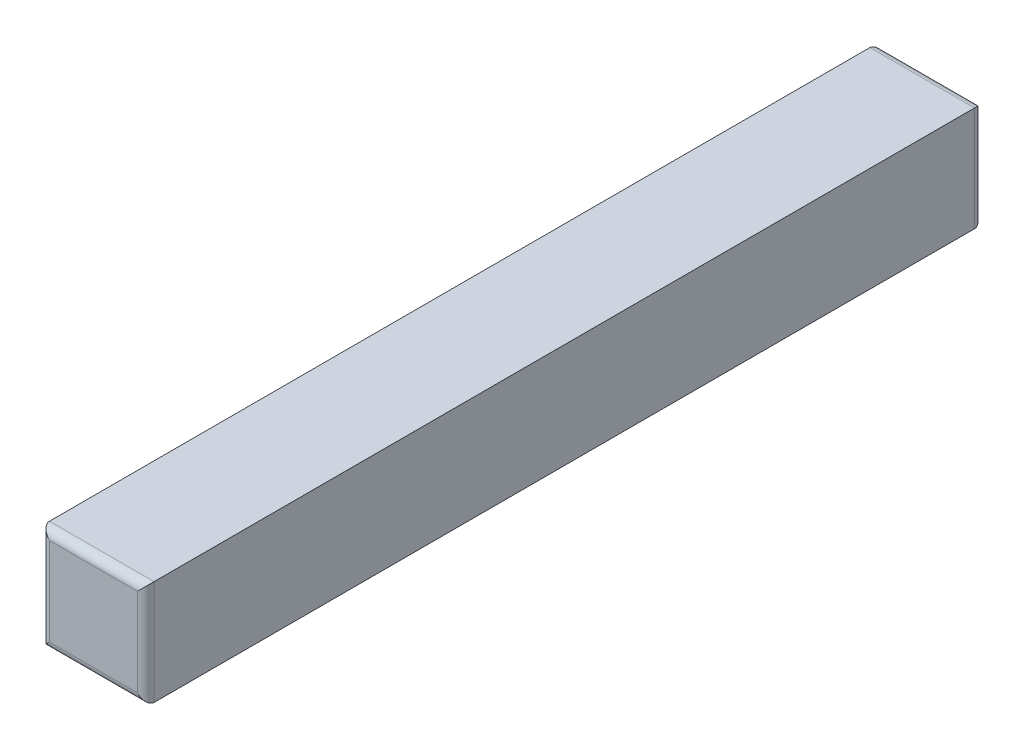
SolidWorks part; units mm, degrees
ref_plane "Front Plane" through (0, 0, 0) normal (0, 0, 1) x (1, 0, 0)
ref_plane "Top Plane" through (0, 0, 0) normal (0, 1, 0) x (1, 0, 0)
ref_plane "Right Plane" through (0, 0, 0) normal (1, 0, 0) x (0, 0, -1)
sketch "Sketch1" plane through (0, 0, 0) normal (0, 0, 1) x (1, 0, 0)
  line L1 (0, 0) -> (3.175, 0)
  line L2 (0, 0) -> (0, 3.175)
  line L3 (0, 3.175) -> (3.175, 3.175)
  line L4 (3.175, 0) -> (3.175, 3.175)
  dimension "D1" = 3.175
  dimension "D2" = 3.175
extrude "Boss-Extrude1" add sketch "Sketch1" against normal blind 25.4
fillet "Fillet1" radius 0.254 4 edges at (1.5875, 3.175, 0) (3.175, 1.5875, 0) (1.5875, 0, 0) (0, 1.5875, 0)
fillet "Fillet2" radius 0.254 4 edges at (1.5875, 0, -25.4) (3.175, 1.5875, -25.4) (1.5875, 3.175, -25.4) (0, 1.5875, -25.4)
